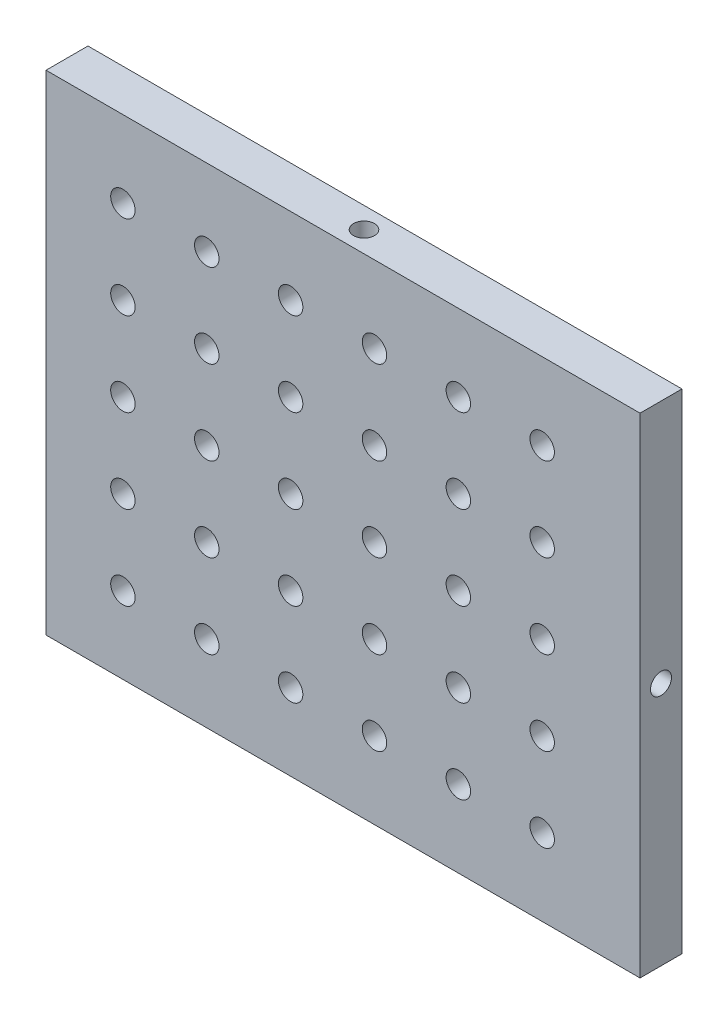
SolidWorks part; units mm, degrees
ref_plane "Plan de face" through (0, 0, 0) normal (0, 0, 1) x (1, 0, 0)
ref_plane "Plan de dessus" through (0, 0, 0) normal (0, 1, 0) x (1, 0, 0)
ref_plane "Plan de droite" through (0, 0, 0) normal (1, 0, 0) x (0, 0, -1)
sketch "Esquisse1" plane through (0, 0, 0) normal (0, 0, 1) x (1, 0, 0)
  line L1 (-42.5, -35) -> (42.5, -35)
  line L2 (-42.5, -35) -> (-42.5, 35)
  line L3 (-42.5, 35) -> (42.5, 35)
  line L4 (42.5, -35) -> (42.5, 35)
  line L5 (-42.5, -35) -> (42.5, 35) construction
  line L6 (-42.5, 35) -> (42.5, -35) construction
  point P0 (0, 0)
  dimension "D1" = 70
  dimension "D2" = 85
extrude "Boss.-Extru.1" add sketch "Esquisse1" along normal blind 6
sketch "Esquisse3" plane through (-42.5, 0, 0) normal (-1, 0, 0) x (0, 0, 1)
  line L0 (-8.5295, 0) -> (14.5295, 0) construction
  line L1 (3, 35) -> (3, -37.4544) construction
  line L2 (6, 35) -> (0, 35) construction
  circle A0 centre (3, 0) radius 1.5
  dimension "D1" = 3
extrude "Enlèv. mat.-Extru.5" cut sketch "Esquisse3" against normal blind 5
mirror "Symétrie1" about plane through (0, 0, 0) normal (1, 0, 0) of "Enlèv. mat.-Extru.5"
sketch "Esquisse5" plane through (0, 0, 0) normal (0, 0, 1) x (1, 0, 0)
  line L0 (-42.5, -35) -> (42.5, -35) construction
  line L2 (-42.5, 35) -> (-42.5, -35) construction
  circle A0 centre (-31.5, -24) radius 1.75
  dimension "D1" = 3.5
  dimension "D2" = 11
  dimension "D3" = 11
extrude "Enlèv. mat.-Extru.6" cut sketch "Esquisse5" along normal up to surface (6 mm away) up to face at (0, 0, 6)
pattern_linear "Répétition linéaire2" count 6 spacing 12 along (1, 0, 0) count 5 spacing 12 along (0, 1, 0) of "Enlèv. mat.-Extru.6"
sketch "Esquisse6" plane through (0, 0, 0) normal (0, 0, 1) x (1, 0, 0)
  circle A2 centre (-19.5, -12) radius 9.8523
  dimension "D1" = 19.7047
extrude "Enlèv. mat.-Extru.7" [suppressed] cut sketch "Esquisse6" along normal up to surface (6 mm away)
sketch "Esquisse8" plane through (0, 35, 0) normal (0, 1, 0) x (1, 0, 0)
  line L0 (-42.5, -3) -> (46.7621, -3) construction
  line L1 (-42.5, -6) -> (-42.5, 0) construction
  line L2 (0, 7.2443) -> (0, -9.709) construction
  circle A0 centre (0, -3) radius 1.5
  dimension "D1" = 3
extrude "Enlèv. mat.-Extru.8" cut sketch "Esquisse8" against normal blind 5
mirror "Symétrie2" about plane through (0, 0, 0) normal (0, 1, 0) of "Enlèv. mat.-Extru.8"
